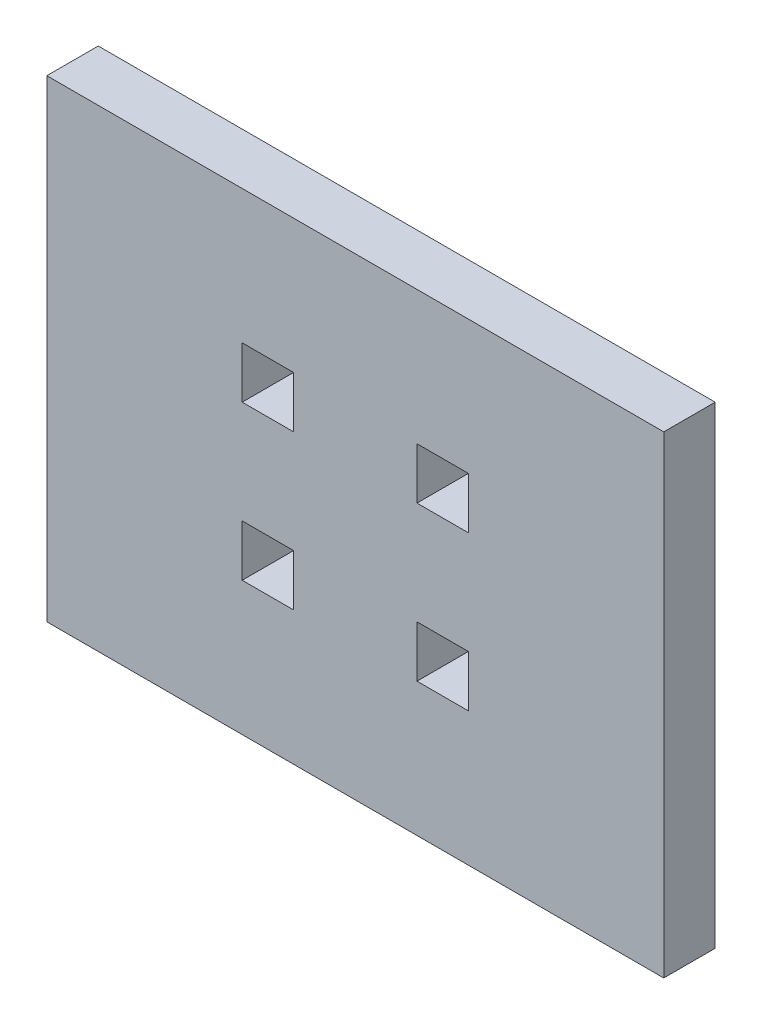
SolidWorks part; units mm, degrees
ref_plane "Plan de face" through (0, 0, 0) normal (0, 0, 1) x (1, 0, 0)
ref_plane "Plan de dessus" through (0, 0, 0) normal (0, 1, 0) x (1, 0, 0)
ref_plane "Plan de droite" through (0, 0, 0) normal (1, 0, 0) x (0, 0, -1)
sketch "Esquisse1" plane through (0, 0, 0) normal (0, 0, 1) x (1, 0, 0)
  line L0 (-9.8936, 25.1875) -> (-14.8936, 25.1875)
  line L1 (-33.8936, 38.1875) -> (26.1064, 38.1875)
  line L2 (-33.8936, 38.1875) -> (-33.8936, -7.8125)
  line L3 (-33.8936, -7.8125) -> (26.1064, -7.8125)
  line L4 (26.1064, 38.1875) -> (26.1064, -7.8125)
  line L5 (-9.8936, 30.1875) -> (2.1064, 30.1875)
  line L6 (-9.8936, 30.1875) -> (-9.8936, 0.1875)
  line L7 (-9.8936, 0.1875) -> (2.1064, 0.1875)
  line L8 (2.1064, 30.1875) -> (2.1064, 0.1875)
  line L9 (-14.8936, 25.1875) -> (-14.8936, 20.1875)
  line L10 (-14.8936, 20.1875) -> (-9.8936, 20.1875)
  line L11 (-9.8936, 20.1875) -> (-9.8936, 25.1875)
  line L12 (-9.8936, 10.1875) -> (-14.8936, 10.1875)
  line L13 (-14.8936, 10.1875) -> (-14.8936, 5.1875)
  line L14 (-14.8936, 5.1875) -> (-9.8936, 5.1875)
  line L15 (-9.8936, 5.1875) -> (-9.8936, 10.1875)
  line L16 (2.1064, 25.1875) -> (7.1064, 25.1875)
  line L17 (7.1064, 25.1875) -> (7.1064, 20.1875)
  line L18 (7.1064, 20.1875) -> (2.1064, 20.1875)
  line L19 (2.1064, 20.1875) -> (2.1064, 25.1875)
  line L20 (2.1064, 10.1875) -> (7.1064, 10.1875)
  line L21 (7.1064, 10.1875) -> (7.1064, 5.1875)
  line L22 (7.1064, 5.1875) -> (2.1064, 5.1875)
  line L23 (2.1064, 5.1875) -> (2.1064, 10.1875)
  dimension "D1" = 60
  dimension "D2" = 46
  dimension "D3" = 30
  dimension "D4" = 12
  dimension "D5" = 8
  dimension "D6" = 5
  dimension "D7" = 5
  dimension "D8" = 10
  dimension "D9" = 5
  dimension "D10" = 5
  dimension "D11" = 5
  dimension "D12" = 5
  dimension "D13" = 5
  dimension "D14" = 5
  dimension "D15" = 5
  dimension "D16" = 24
extrude "Boss.-Extru.1" add sketch "Esquisse1" along normal blind 5 contours L4 L1 L2 L3 L21 L22 L8 L7 L6 L14 L13 L12 L10 L9 L0 L5 L16 L17 L18 L20 | L8 L5 L6 L7
